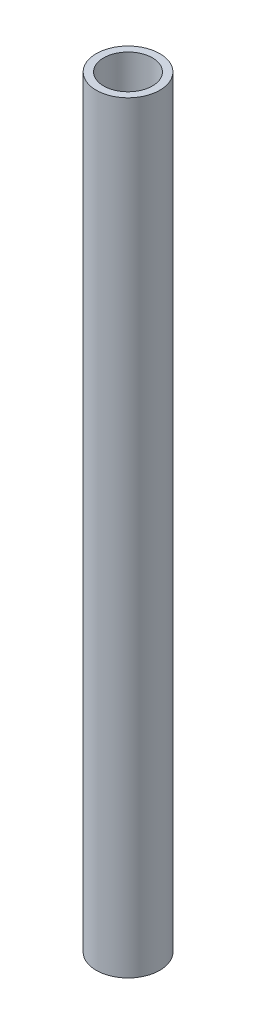
SolidWorks part; units mm, degrees
ref_plane "Front Plane" through (0, 0, 0) normal (0, 0, 1) x (1, 0, 0)
ref_plane "Top Plane" through (0, 0, 0) normal (0, 1, 0) x (1, 0, 0)
ref_plane "Right Plane" through (0, 0, 0) normal (1, 0, 0) x (0, 0, -1)
sketch "Sketch1" plane through (0, 0, 0) normal (0, 1, 0) x (1, 0, 0)
  circle A0 centre (0, 0) radius 6.35
  circle A1 centre (0, 0) radius 4.8768
  dimension "D1" = 12.7
  dimension "D2" = 1.4732
extrude "Boss-Extrude1" add sketch "Sketch1" along normal blind 152.4
